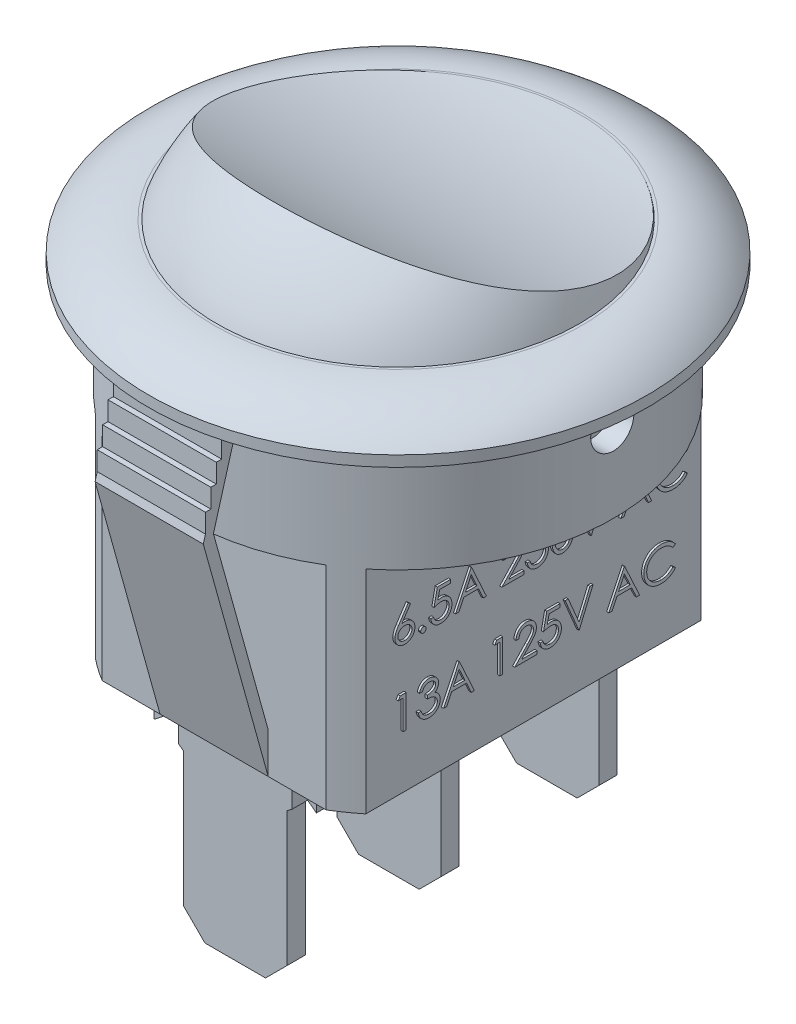
SolidWorks part; units mm, degrees
ref_plane "Front Plane" through (0, 0, 0) normal (0, 0, 1) x (1, 0, 0)
ref_plane "Top Plane" through (0, 0, 0) normal (0, 1, 0) x (1, 0, 0)
ref_plane "Right Plane" through (0, 0, 0) normal (1, 0, 0) x (0, 0, -1)
sketch "Sketch1" plane through (0, 0, 0) normal (0, 0, 1) x (1, 0, 0)
  line L0 (0, -12.9915) -> (0, 12.9915) construction
  line L1 (0, -8.4) -> (9.95, -8.4)
  line L2 (9.95, -8.4) -> (9.95, 6.6)
  line L3 (9.95, 6.6) -> (11.5, 6.6)
  line L4 (11.5, 6.6) -> (11.5, 7.1)
  line L5 (8.5, 8.4) -> (0, 8.4)
  line L6 (0, 8.4) -> (0, -8.4)
  arc A0 (11.5, 7.1) -> (8.5, 8.4) centre (8.5, 4.2885) ccw
  dimension "D1" = 0.5
  dimension "D2" = 23
  dimension "D3" = 19.9
  dimension "D4" = 17
  dimension "D5" = 1.8
  dimension "D6" = 15
revolve "Revolve1" add sketch "Sketch1" angle 360 about L0
sketch "Sketch2" plane through (0, -8.4, 0) normal (0, -1, 0) x (1, 0, 0)
  line L1 (-6.25, 8.5) -> (6.25, 8.5)
  line L2 (-6.25, 8.5) -> (-6.25, -8.5)
  line L3 (-6.25, -8.5) -> (6.25, -8.5)
  line L4 (6.25, 8.5) -> (6.25, -8.5)
  line L5 (-6.25, 8.5) -> (6.25, -8.5) construction
  line L6 (-6.25, -8.5) -> (6.25, 8.5) construction
  point P0 (0, 0)
  dimension "D1" = 12.5
  dimension "D2" = 17
extrude "Cut-Extrude1" cut sketch "Sketch2" against normal blind 9.8 flip side to cut
sketch "Sketch3" plane through (0, 0, 0) normal (1, 0, 0) x (0, 0, -1)
  line L0 (-8.5, -8.4) -> (-11.5, 2.4)
  line L1 (-11.5, 2.4) -> (-10.3, 6.6) construction
  line L2 (-8.5, -8.4) -> (-8.5, -6.5318)
  line L3 (-8.5, 1.4) -> (-8.5, -8.4) construction
  line L4 (-8.5, -6.5318) -> (-11.0318, 2.5827)
  line L5 (0, 0) -> (0, -11.6315) construction
  line L6 (-11.5, 6.6) -> (11.5, 6.6) construction
  line L7 (-10.3, 6.6) -> (-9.884, 6.6)
  line L8 (-9.884, 6.6) -> (-11.0318, 2.5827)
  line L9 (-10.3, 6.6) -> (-10.4, 6.25)
  line L10 (-10.4, 6.25) -> (-10.65, 6.25)
  line L11 (-10.65, 6.25) -> (-10.65, 5.375)
  line L12 (-10.65, 5.375) -> (-10.9, 5.375)
  line L13 (-10.9, 5.375) -> (-10.9, 4.5)
  line L14 (-10.9, 4.5) -> (-11.15, 4.5)
  line L15 (-11.15, 4.5) -> (-11.15, 3.625)
  line L16 (-11.15, 3.625) -> (-11.4, 3.625)
  line L17 (-11.4, 3.625) -> (-11.4, 2.75)
  line L18 (-11.4, 2.75) -> (-11.5, 2.4)
  dimension "D1" = 0.5
  dimension "D2" = 23
  dimension "D3" = 0.4
  dimension "D4" = 20.6
  dimension "D5" = 10.8
  dimension "D6" = 0.25
  dimension "D7" = 0.25
  dimension "D8" = 0.25
  dimension "D9" = 0.25
extrude "Boss-Extrude1" add sketch "Sketch3" along normal mid plane 5
mirror "Mirror1" about plane through (0, 0, 0) normal (0, 0, 1) of "Boss-Extrude1"
sketch "Sketch4" plane through (0, 0, 0) normal (0, 0, 1) x (1, 0, 0)
  line L0 (-3.75, -8.4) -> (-3.75, -9.7231)
  line L1 (-2.5, -8.4) -> (-5.1723, -8.4) construction
  line L2 (-3.75, -9.7231) -> (-2.625, -8.849)
  line L3 (-2.625, -8.849) -> (-2.625, -10.1343)
  line L4 (-2.625, -10.1343) -> (-2.4, -10.3)
  line L5 (-2.4, -10.3) -> (-2.4, -16.5)
  line L6 (-1.4, -17.5) -> (1.4, -17.5)
  line L7 (2.4, -16.5) -> (2.4, -10.3)
  line L8 (2.4, -10.3) -> (2.625, -10.1343)
  line L9 (2.625, -10.1343) -> (2.625, -8.849)
  line L10 (2.625, -8.849) -> (3.75, -9.7231)
  line L11 (3.75, -9.7231) -> (3.75, -8.4)
  line L12 (5.1723, -8.4) -> (2.5, -8.4) construction
  line L13 (3.75, -8.4) -> (-3.75, -8.4)
  line L14 (0, 0) -> (0, -17.5) construction
  line L15 (-2.4, -16.5) -> (-1.4, -17.5)
  line L16 (1.4, -17.5) -> (2.4, -16.5)
  point P8 (-2.4, -17.5)
  point P9 (2.4, -17.5)
  dimension "D1" = 7.5
  dimension "D2" = 5.25
  dimension "D3" = 1.7343
  dimension "D4" = 7.2
  dimension "D5" = 9.1
  dimension "D6" = 4.8
extrude "Boss-Extrude2" add sketch "Sketch4" along normal mid plane 0.85
pattern_linear "LPattern1" count 2 spacing 7.1 along (0, 0, 1) of "Boss-Extrude2"
pattern_linear "LPattern2" count 2 spacing 7.3 along (0, 0, -1) of "Boss-Extrude2"
ref_plane "Plane1" through (-9.95, 0, 0) normal (-1, 0, 0) x (0, 0, 1)
sketch "Sketch7" plane through (-9.95, 0, 0) normal (-1, 0, 0) x (0, 0, 1)
  line L0 (-9.884, 6.6) -> (9.884, 6.6) construction
  circle A0 centre (0, 5.1) radius 1
  dimension "D1" = 2
  dimension "D2" = 1.5
extrude "Cut-Extrude3" cut sketch "Sketch7" against normal blind 1
sketch "Sketch5" plane through (0, 0, 0) normal (0, 0, 1) x (1, 0, 0)
  line L0 (1.1442, 6.6) -> (9.95, 6.6) construction
  line L1 (0, 0) -> (0, 5.1) construction
  line L2 (8.9443, 4.1) -> (0, 4.1)
  line L3 (0, 4.1) -> (0, 14.1)
  arc A0 (8.9443, 4.1) -> (0, 14.1) centre (0, 5.1) ccw
  dimension "D2" = 18
  dimension "D1" = 1.5
  dimension "D3" = 2.5
revolve "Revolve2" add sketch "Sketch5" angle 360 about L1
sketch "Sketch6" plane through (0, 0, 0) normal (1, 0, 0) x (0, 0, -1)
  line L0 (8.5, 8.4) -> (-12.1732, 8.4) construction
  arc A0 (-5.7784, 12) -> (8.3584, 8.4372) centre (7.44, 34.6211) ccw
  arc A1 (8.3732, 8.4) -> (-5.7784, 12) centre (0, 5.1) ccw
  arc A2 (8.3732, 8.4) -> (-8.3732, 8.4) centre (0, 5.1) ccw construction
  dimension "D2" = 26.2
  dimension "D1" = 3.6
extrude "Cut-Extrude2" cut sketch "Sketch6" against normal through all both and the other way through all contours A0 A1
mirror "Mirror2" about plane through (0, 0, 0) normal (1, 0, 0) of "Cut-Extrude3"
sketch "Sketch8" plane through (6.25, 0, 0) normal (1, 0, 0) x (0, 0, -1)
  text T0 "6.5A 250V AC\r\n13A 125V AC" font "Century Gothic" height 1.5
extrude "Boss-Extrude3" add sketch "Sketch8" along normal blind 0.1
